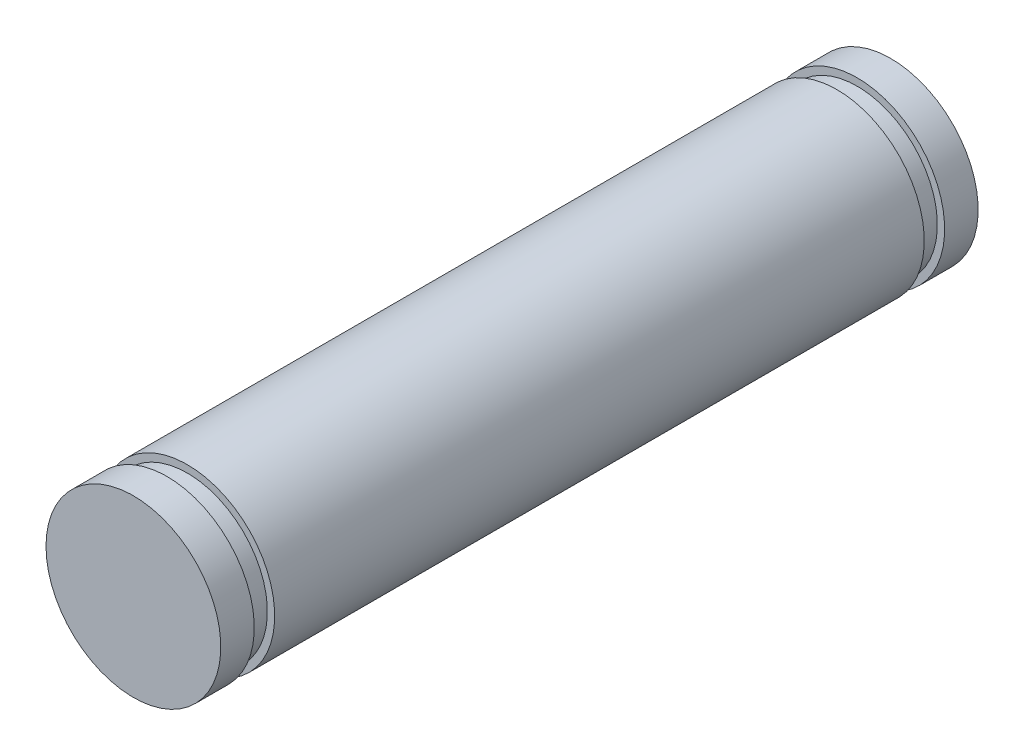
SolidWorks part; units mm, degrees
ref_plane "정면" through (0, 0, 0) normal (0, 0, 1) x (1, 0, 0)
ref_plane "윗면" through (0, 0, 0) normal (0, 1, 0) x (1, 0, 0)
ref_plane "우측면" through (0, 0, 0) normal (1, 0, 0) x (0, 0, -1)
sketch "스케치1" plane through (0, 0, 0) normal (0, 0, 1) x (1, 0, 0)
  circle A0 centre (0, 0) radius 3
  dimension "D1" = 6
extrude "보스-돌출1" add sketch "스케치1" along normal blind 26
ref_plane "평면2" through (0, 0, 13) normal (0, 0, -1) x (-1, 0, 0)
ref_plane "평면1" through (0, 0, 1.5) normal (0, 0, -1) x (-1, 0, 0)
sketch "스케치2" plane through (0, 0, 1.5) normal (0, 0, -1) x (-1, 0, 0)
  circle A0 centre (0, 0) radius 2.75
  circle A1 centre (0, 0) radius 3
  circle A2 centre (0, 0) radius 3
  dimension "D1" = 0
  dimension "D2" = 0.25
extrude "컷-돌출1" cut sketch "스케치2" against normal blind 0.35 and the other way blind 0.35 contours A0 | A2
mirror "대칭 복사1" about plane through (0, 0, 13) normal (0, 0, -1) of "컷-돌출1"
